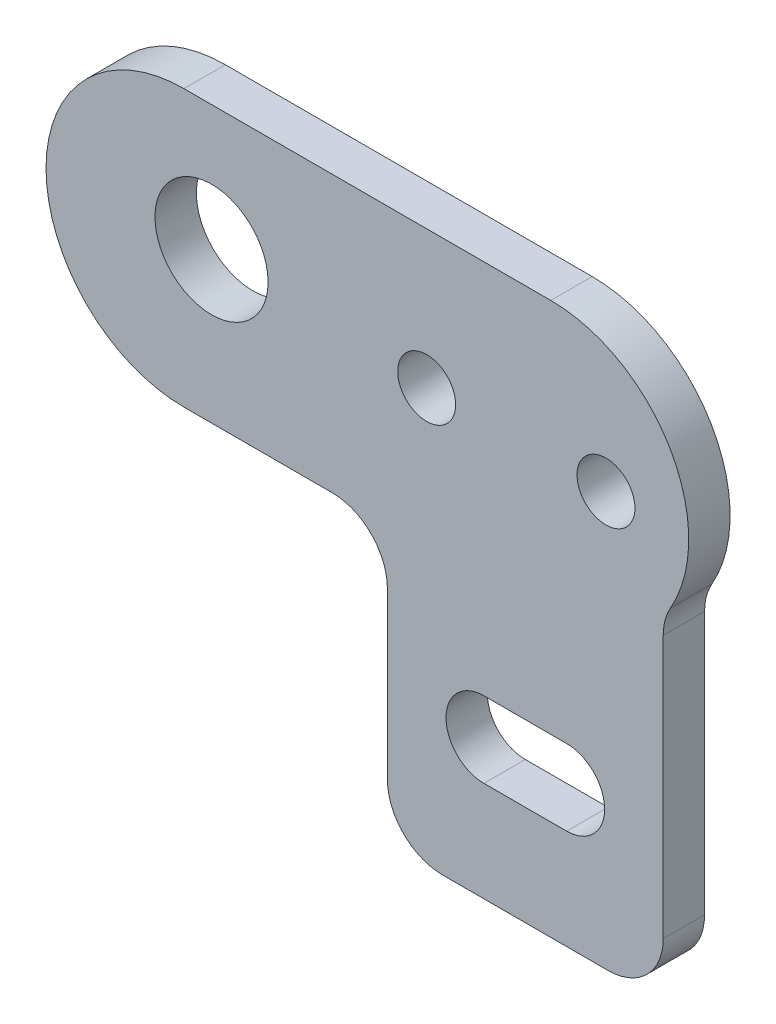
SolidWorks part; units mm, degrees
ref_plane "Front Plane" through (0, 0, 0) normal (0, 0, 1) x (1, 0, 0)
ref_plane "Top Plane" through (0, 0, 0) normal (0, 1, 0) x (1, 0, 0)
ref_plane "Right Plane" through (0, 0, 0) normal (1, 0, 0) x (0, 0, -1)
sketch "Sketch1" plane through (0, 0, 0) normal (0, 0, 1) x (1, 0, 0)
  line L0 (-13.3, 0) -> (13.3, 0) construction
  line L1 (-13.3, 10) -> (13.3, 10)
  line L2 (-13.3, -10) -> (13.3, -10)
  line L3 (1.45, -10) -> (1.45, -30)
  line L4 (1.45, -30) -> (21.45, -30)
  line L5 (21.45, -30) -> (21.45, -5.7946)
  arc A0 (-13.3, 10) -> (-13.3, -10) centre (-13.3, 0) ccw
  arc A1 (13.3, -10) -> (13.3, 10) centre (13.3, 0) ccw
  point P2 (0, 0)
  dimension "D1" = 46.6
  dimension "D2" = 20
  dimension "D3" = 40
  dimension "D4" = 20
  dimension "D5" = 1.85
extrude "Boss-Extrude1" add sketch "Sketch1" along normal mid plane 3
fillet "Fillet1" radius 4 4 edges at (21.45, -30, 0) (1.45, -30, 0) (1.45, -10, 0) (21.45, -5.7946, 0)
sketch "Sketch2" plane through (0, 0, 1.5) normal (0, 0, 1) x (1, 0, 0)
  line L0 (-13.3, 10) -> (13.3, 10) construction
  line L1 (4.3, 0) -> (17.3, 0) construction
  line L2 (0, 0) -> (4.3, 0) construction
  line L3 (11.45, -30) -> (11.45, -20) construction
  line L4 (5.45, -30) -> (17.45, -30) construction
  line L5 (8.45, -20) -> (14.45, -20) construction
  line L6 (8.45, -17.25) -> (14.45, -17.25)
  line L7 (8.45, -22.75) -> (14.45, -22.75)
  circle A0 centre (-11.3, 0.9) radius 4.1
  arc A1 (-13.3, 10) -> (-13.3, -10) centre (-13.3, 0) ccw construction
  circle A2 centre (4.3, 0) radius 2.1
  circle A3 centre (17.3, 0) radius 2.1
  arc A5 (21.9786, -4.9681) -> (13.3, 10) centre (13.3, 0) ccw construction
  arc A6 (8.45, -17.25) -> (8.45, -22.75) centre (8.45, -20) ccw
  arc A7 (14.45, -22.75) -> (14.45, -17.25) centre (14.45, -20) ccw
  point P22 (11.45, -20)
  dimension "D1" = 8.2
  dimension "D4" = 4.2
  dimension "D8" = 11.5
  dimension "D2" = 5
  dimension "D3" = 12
  dimension "D5" = 13
  dimension "D6" = 6
  dimension "D7" = 5.5
  dimension "D9" = 7.25
extrude "Cut-Extrude1" cut sketch "Sketch2" against normal through all
move or copy body "Body-Move/Copy1" [suppressed] bodies to move or copy 102
